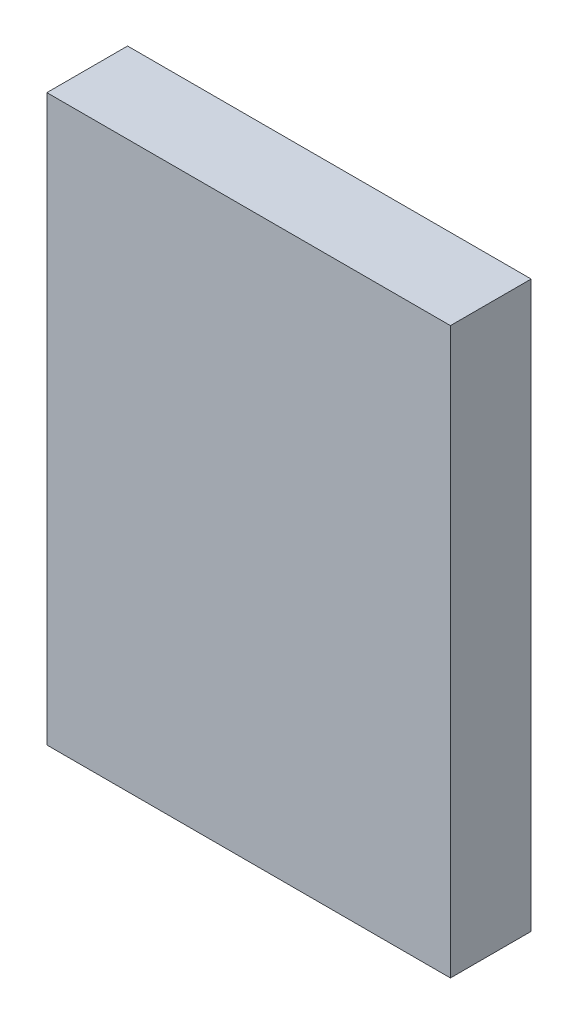
SolidWorks part; units mm, degrees
ref_plane "Front Plane" through (0, 0, 0) normal (0, 0, 1) x (1, 0, 0)
ref_plane "Top Plane" through (0, 0, 0) normal (0, 1, 0) x (1, 0, 0)
ref_plane "Right Plane" through (0, 0, 0) normal (1, 0, 0) x (0, 0, -1)
sketch "Sketch2" plane through (0, 0, 0) normal (0, 0, 1) x (1, 0, 0)
  line L1 (-12.5, -17.5) -> (12.5, -17.5)
  line L2 (-12.5, -17.5) -> (-12.5, 17.5)
  line L3 (-12.5, 17.5) -> (12.5, 17.5)
  line L4 (12.5, -17.5) -> (12.5, 17.5)
  line L5 (-12.5, -17.5) -> (12.5, 17.5) construction
  line L6 (-12.5, 17.5) -> (12.5, -17.5) construction
  point P0 (0, 0)
  dimension "D1" = 25
  dimension "D2" = 35
extrude "Boss-Extrude1" add sketch "Sketch2" along normal blind 5
